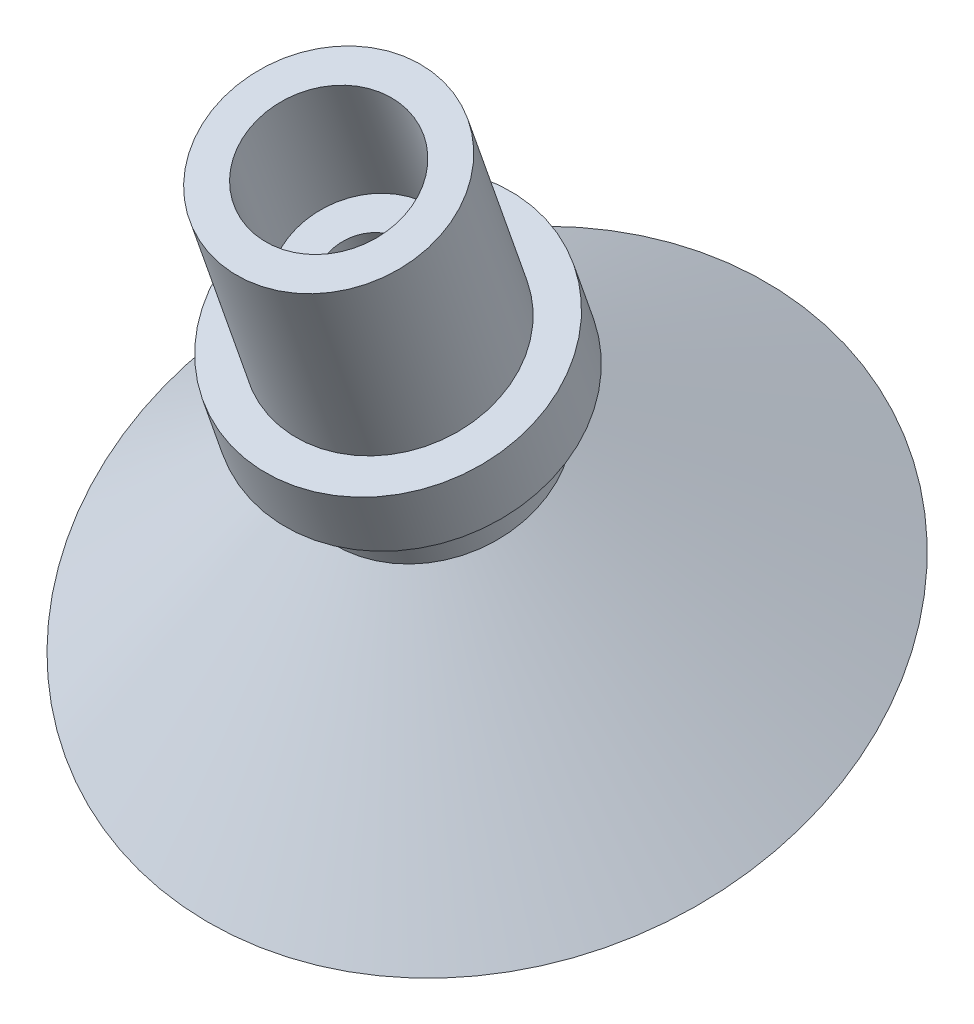
SolidWorks part; units mm, degrees
other "Inlet Fairlead Liner"
ref_plane "Front Plane" through (0, 0, 0) normal (0, 0, 1) x (1, 0, 0)
ref_plane "Top Plane" through (0, 0, 0) normal (0, 1, 0) x (1, 0, 0)
ref_plane "Right Plane" through (0, 0, 0) normal (1, 0, 0) x (0, 0, -1)
sketch3d "Inlet Fairlead Liner Feature axis line"
  line L0 (-17.2536, -35.9152, 3.8742) -> (-19.3297, -54.2359, -3.8742) construction
ref_axis "Inlet Fairlead Liner Feature axis" through (-17.2536, -35.9152, 3.8742) along (-0.1038, -0.916, -0.3874)
sketch3d "Inlet Fairlead Liner Profile datum points"
  point P0 (-18.2917, -45.0756, 0)
  point P1 (-27.9509, -45.0756, 2.5882)
  point P2 (-19.3297, -54.2359, -3.8742)
ref_plane "Inlet Fairlead Liner Profile plane" through (3.2582, -5.512, 12.1598) normal (0.2371, -0.4011, 0.8848) x (0.9715, 0.0979, -0.2159)
sketch "Inlet Fairlead Liner Profile" plane through (3.2582, -5.512, 12.1598) normal (0.2371, -0.4011, 0.8848) x (0.9715, 0.0979, -0.2159)
  line L0 (-23.152, -30.8928) -> (-23.5794, -34.8699)
  line L1 (-23.5794, -34.8699) -> (-22.6349, -34.9714)
  line L2 (-22.6349, -34.9714) -> (-23.0623, -38.9485)
  line L3 (-30.8771, -46.1547) -> (-31.8714, -46.0478)
  line L4 (-31.8714, -46.0478) -> (-25.1651, -40.734)
  line L5 (-25.1651, -40.734) -> (-24.9514, -38.7454)
  line L6 (-24.9514, -38.7454) -> (-25.9457, -38.6386)
  line L7 (-25.9457, -38.6386) -> (-25.732, -36.65)
  line L8 (-25.732, -36.65) -> (-24.7377, -36.7569)
  line L9 (-24.7377, -36.7569) -> (-24.0966, -30.7912)
  line L10 (-24.0966, -30.7912) -> (-23.152, -30.8928)
  arc A0 (-30.8771, -46.1547) -> (-24.2703, -40.8302) centre (-30.2359, -40.189) ccw
  spline S0 degree 3 poles (-23.0623, -38.9485) (-23.1335, -39.6113) (-24.1991, -40.1673) (-24.2703, -40.8302) knots 0 0 0 0 1 1 1 1
revolve "Inlet Fairlead Liner Feature" add sketch "Inlet Fairlead Liner Profile" angle 360 about axis through (-17.2536, -35.9152, 3.8742) along (-0.1038, -0.916, -0.3874)
